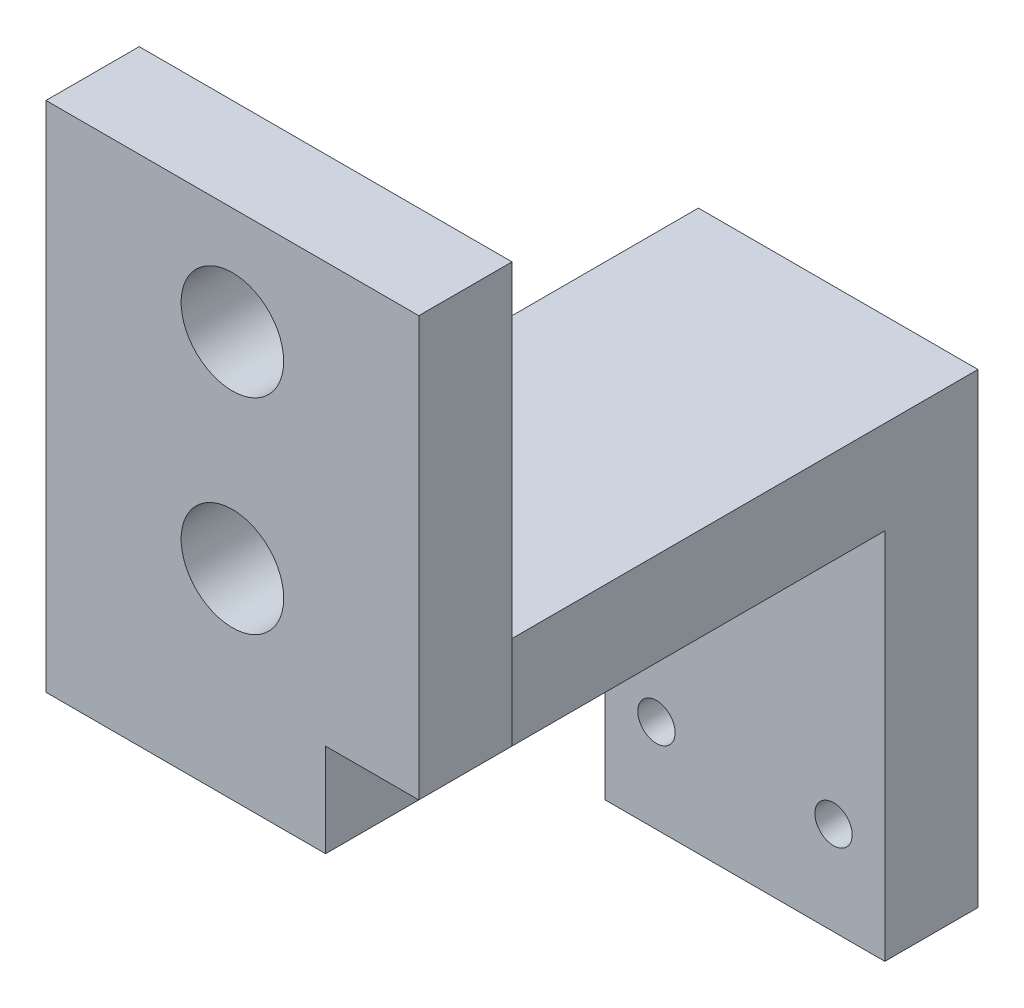
SolidWorks part; units mm, degrees
ref_plane "Plan de face" through (0, 0, 0) normal (0, 0, 1) x (1, 0, 0)
ref_plane "Plan de dessus" through (0, 0, 0) normal (0, 1, 0) x (1, 0, 0)
ref_plane "Plan de droite" through (0, 0, 0) normal (1, 0, 0) x (0, 0, -1)
sketch "Esquisse1" plane through (0, 0, 0) normal (0, 0, 1) x (1, 0, 0)
  line L0 (-27.8251, 2.2177) -> (-27.8251, -8.7823) construction
  line L2 (-37.8251, 7.9677) -> (-37.8251, -14.5323)
  line L8 (-37.8251, 7.9677) -> (-17.8251, 7.9677)
  line L9 (-17.8251, 7.9677) -> (-17.8251, -14.5323)
  line L12 (-37.8251, -14.5323) -> (-17.8251, -14.5323)
  circle A0 centre (-27.8251, 2.2177) radius 2.75
  circle A1 centre (-27.8251, -8.7823) radius 2.75
  point P8 (-27.8251, -3.2823)
  point P10 (-37.8251, -3.2823)
  point P17 (-27.8251, 7.9677)
  dimension "D3" = 5.5
  dimension "D1" = 11
  dimension "D2" = 22.5
  dimension "D5" = 20
extrude "Boss.-Extru.1" add sketch "Esquisse1" along normal blind 5
sketch "Esquisse4" plane through (-37.8251, 0, 0) normal (-1, 0, 0) x (0, 0, 1)
  line L0 (5, -14.5323) -> (-30, -14.5323)
  line L1 (-30, -14.5323) -> (-30, -39.5323)
  line L2 (-30, -39.5323) -> (-25, -39.5323)
  line L3 (-25, -39.5323) -> (-25, -19.5323)
  line L4 (-25, -19.5323) -> (5, -19.5323)
  line L5 (5, -19.5323) -> (5, -14.5323)
  line L6 (5, -14.5323) -> (0, -14.5323) construction
  point P3 (3.2595, -15.7823)
  point P8 (-30, -14.5323)
  point P12 (0, 0)
  dimension "D1" = 5
  dimension "D2" = 5
  dimension "D3" = 30
extrude "Boss.-Extru.2" add sketch "Esquisse4" against normal blind 15
sketch "Esquisse3" plane through (0, 0, -30) normal (0, 0, 1) x (1, 0, 0)
  line L0 (-25.5751, -34.5323) -> (-35.0751, -34.5323) construction
  line L3 (-22.8251, -14.5323) -> (-37.8251, -14.5323) construction
  line L4 (-22.8251, -39.5323) -> (-37.8251, -39.5323) construction
  circle A0 centre (-25.5751, -34.5323) radius 1
  circle A1 centre (-35.0751, -34.5323) radius 1
  point P4 (-31.7717, -26.2377)
  point P5 (-30.3251, -34.5323)
  point P8 (-30.3251, -14.5323)
  dimension "D4" = 2
  dimension "D1" = 9.5
  dimension "D2" = 5
extrude "Enlèv. mat.-Extru.1" cut sketch "Esquisse3" along normal up to next
